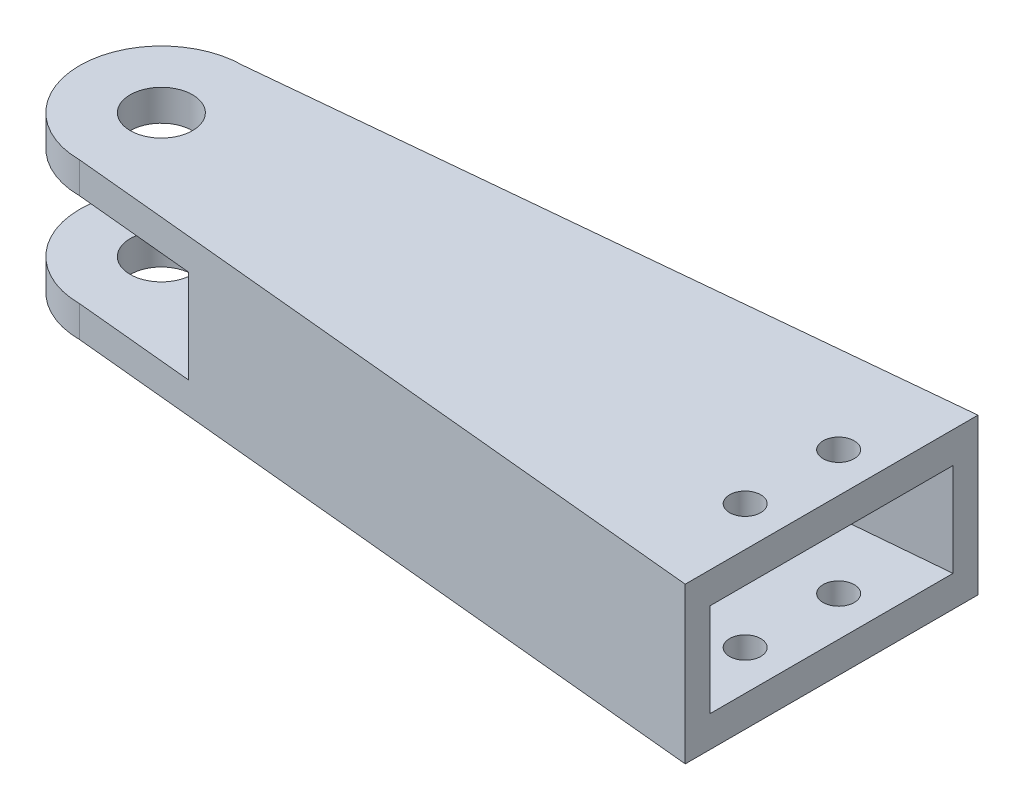
SolidWorks part; units mm, degrees
ref_plane "Front Plane" through (0, 0, 0) normal (0, 0, 1) x (1, 0, 0)
ref_plane "Top Plane" through (0, 0, 0) normal (0, 1, 0) x (1, 0, 0)
ref_plane "Right Plane" through (0, 0, 0) normal (1, 0, 0) x (0, 0, -1)
sketch "Sketch1" plane through (0, 0, 0) normal (0, 1, 0) x (1, 0, 0)
  line L0 (0, 18.805) -> (0, -18.805)
  line L1 (-153.3261, 0) -> (49.2947, 0) construction
  line L2 (-86.1, 10.5) -> (0, 18.805)
  line L3 (-86.1, -10.5) -> (0, -18.805)
  arc A0 (-86.1, 10.5) -> (-86.1, -10.5) centre (-86.1, 0) ccw
  circle A1 centre (-86.1, 0) radius 4
  circle A2 centre (-5.1, 6.005) radius 2
  circle A3 centre (-5.1, -6.005) radius 2
  dimension "D2" = 8
  dimension "D3" = 21
  dimension "D4" = 86.1
  dimension "D5" = 4
  dimension "D6" = 12.8
  dimension "D7" = 5.1
  dimension "D1" = 37.61
extrude "Boss-Extrude1" add sketch "Sketch1" along normal mid plane 20
sketch "Sketch3" plane through (0, 0, 0) normal (1, 0, 0) x (0, 0, -1)
  line L1 (-15.595, 6) -> (15.595, 6)
  line L2 (-15.595, 6) -> (-15.595, -6)
  line L3 (-15.595, -6) -> (15.595, -6)
  line L4 (15.595, 6) -> (15.595, -6)
  line L5 (-15.595, 6) -> (15.595, -6) construction
  line L6 (-15.595, -6) -> (15.595, 6) construction
  point P0 (0, 0)
  dimension "D1" = 31.19
  dimension "D2" = 12
extrude "Cut-Extrude1" cut sketch "Sketch3" against normal blind 20
draft "Draft1" type of draft neutral plane draft angle 5.033 faces to draft 2 face at (-10, 0, 15.595) face at (-10, 0, -15.595) neutral plane through (0, 10, -18.805) neutral plane normal (1, 0, 0) parameters "D1"=5.033
sketch "Sketch4" plane through (0, 0, 0) normal (0, 0, 1) x (1, 0, 0)
  line L1 (-70.6, -6) -> (-96.6, -6)
  line L2 (-70.6, -6) -> (-70.6, 6)
  line L3 (-70.6, 6) -> (-96.6, 6)
  line L4 (-96.6, -6) -> (-96.6, 6)
  line L5 (-119.8524, 0) -> (-27.6389, 0) construction
  dimension "D1" = 12
  dimension "D2" = 26
extrude "Cut-Extrude2" cut sketch "Sketch4" against normal through all both and the other way through all
